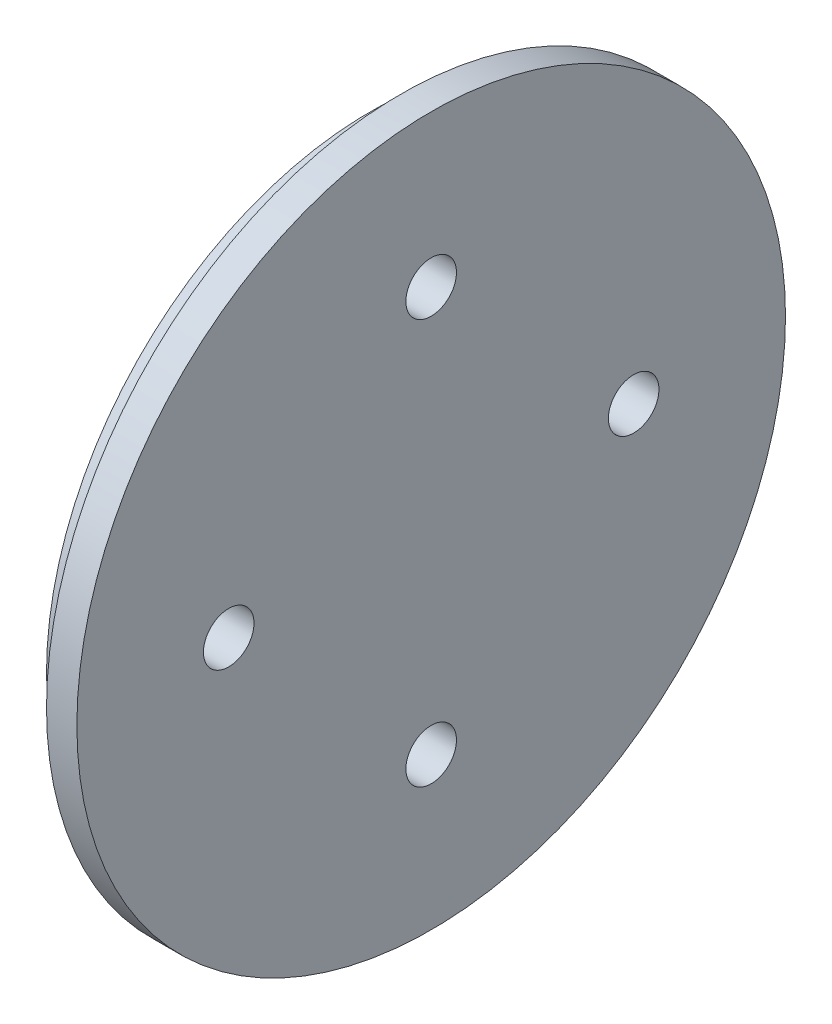
SolidWorks part; units mm, degrees
material "2024-T4"
ref_plane "Спереди" through (0, 0, 0) normal (0, 0, 1) x (1, 0, 0)
ref_plane "Сверху" through (0, 0, 0) normal (0, 1, 0) x (1, 0, 0)
ref_plane "Справа" through (0, 0, 0) normal (1, 0, 0) x (0, 0, -1)
sketch "Эскиз1" plane through (0, 0, 0) normal (0, 0, 1) x (1, 0, 0)
  line L0 (0, 0) -> (6, 0) construction
  line L1 (6, 0) -> (6, 35)
  line L2 (6, 35) -> (3, 35)
  line L3 (3, 35) -> (3, 32)
  line L4 (3, 32) -> (0, 32)
  line L5 (0, 32) -> (0, 15)
  line L6 (0, 15) -> (2, 15)
  line L7 (2, 15) -> (2, 0)
  line L8 (6, 0) -> (2, 0)
  dimension "D1" = 6
  dimension "D2" = 2
  dimension "D3" = 35
  dimension "D4" = 32
  dimension "D5" = 3
  dimension "D6" = 30
revolve "Повернуть1" add sketch "Эскиз1" angle 360 about L0
sketch "Эскиз2" plane through (0, 0, 0) normal (-1, 0, 0) x (0, 0, 1)
  circle A0 centre (0, 20) radius 2.5
  dimension "D2" = 5
  dimension "D1" = 20
extrude "Вырез-Вытянуть1" cut sketch "Эскиз2" against normal blind 33.3 contours A0
pattern_circular "Круговой массив1" count 4 over 360 about axis through (0, 0, 0) along (1, 0, 0) of "Вырез-Вытянуть1"
